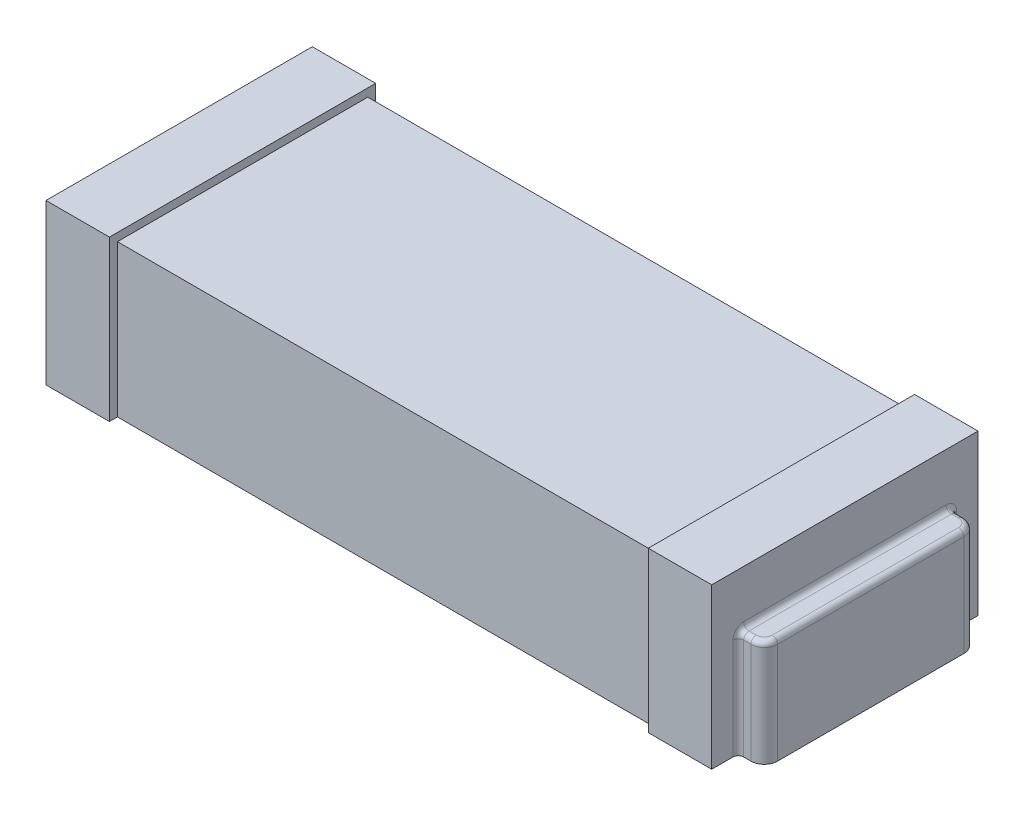
SolidWorks part; units mm, degrees
ref_plane "Plan de face" through (0, 0, 0) normal (0, 0, 1) x (1, 0, 0)
ref_plane "Plan de dessus" through (0, 0, 0) normal (0, 1, 0) x (1, 0, 0)
ref_plane "Plan de droite" through (0, 0, 0) normal (1, 0, 0) x (0, 0, -1)
sketch "Esquisse1" plane through (0, 0, 0) normal (0, 1, 0) x (1, 0, 0)
  line L1 (1.25, -0.5) -> (-1.25, -0.5)
  line L2 (1.25, -0.5) -> (1.25, 0.5)
  line L3 (1.25, 0.5) -> (-1.25, 0.5)
  line L4 (-1.25, -0.5) -> (-1.25, 0.5)
  line L5 (1.25, -0.5) -> (-1.25, 0.5) construction
  line L6 (1.25, 0.5) -> (-1.25, -0.5) construction
  point P0 (0, 0)
  dimension "D1" = 2.5
  dimension "D2" = 1
extrude "Boss.-Extru.1" add sketch "Esquisse1" along normal blind 0.6
sketch "Esquisse2" plane through (0, 0.6, 0) normal (0, 1, 0) x (1, 0, 0)
  line L0 (1.25, 0.5) -> (-1.25, 0.5) construction
  line L1 (1.0118, -0.5) -> (-1.0118, -0.5)
  line L2 (1.0118, -0.5) -> (1.0118, 0.5)
  line L3 (1.0118, 0.5) -> (-1.0118, 0.5)
  line L4 (-1.0118, -0.5) -> (-1.0118, 0.5)
  line L5 (1.0118, -0.5) -> (-1.0118, 0.5) construction
  line L6 (1.0118, 0.5) -> (-1.0118, -0.5) construction
  point P0 (0, 0)
extrude "Enlèv. mat.-Extru.1" cut sketch "Esquisse2" against normal blind 0.03
sketch "Esquisse3" plane through (0, 0, 0) normal (0, 1, 0) x (1, 0, 0)
  line L0 (1.25, -0.5) -> (1.25, 0.5) construction
  line L1 (1.25, 0.4) -> (1.2971, 0.4)
  line L2 (1.25, 0.4) -> (1.25, -0.4)
  line L3 (1.25, -0.4) -> (1.2971, -0.4)
  line L4 (1.3471, 0.35) -> (1.3471, -0.35)
  line L5 (1.25, 0.5) -> (1.0118, 0.5) construction
  line L6 (1.0118, -0.5) -> (1.25, -0.5) construction
  arc A0 (1.2971, -0.4) -> (1.3471, -0.35) centre (1.2971, -0.35) ccw
  arc A1 (1.2971, 0.4) -> (1.3471, 0.35) centre (1.2971, 0.35) cw
  dimension "D1" = 0.05
  dimension "D2" = 0.1
  dimension "D3" = 0.1
extrude "Boss.-Extru.2" add sketch "Esquisse3" along normal blind 0.4
fillet "Congé1" radius 0.02 8 edges at (1.25, 0.2, -0.4) (1.25, 0.2, 0.4) (1.2736, 0.4, -0.4) (1.3325, 0.4, -0.3854) (1.3471, 0.4, 0) (1.3325, 0.4, 0.3854) (1.2736, 0.4, 0.4) (1.25, 0.4, 0)
mirror "Symétrie2" about plane through (0, 0, 0) normal (1, 0, 0) of "Congé1", "Boss.-Extru.2"
sketch "Esquisse5" plane through (0, 0, -0.5) normal (0, 0, -1) x (-1, 0, 0)
  line L0 (-1.0118, 0.57) -> (-1.0118, 0)
  line L1 (1.0118, 0.57) -> (1.0118, 0)
  line L8 (1.25, 0.6) -> (1.0118, 0.6)
  line L9 (1.0118, 0.6) -> (1.0118, 0.57)
  line L10 (1.0118, 0.57) -> (-1.0118, 0.57)
  line L11 (-1.0118, 0.57) -> (-1.0118, 0.6)
  line L12 (-1.0118, 0.6) -> (-1.25, 0.6)
  line L13 (-1.25, 0.6) -> (-1.25, 0)
  line L14 (-1.25, 0) -> (1.25, 0)
  line L15 (1.25, 0) -> (1.25, 0.6)
  line L18 (1.0118, 0.57) -> (-1.0118, 0.57)
  line L22 (-1.0118, 0) -> (1.0118, 0)
  dimension "D1" = 0
extrude "Enlèv. mat.-Extru.2" cut sketch "Esquisse5" against normal blind 0.03
mirror "Symétrie3" about plane through (0, 0, 0) normal (0, 0, 1) of "Enlèv. mat.-Extru.2"
